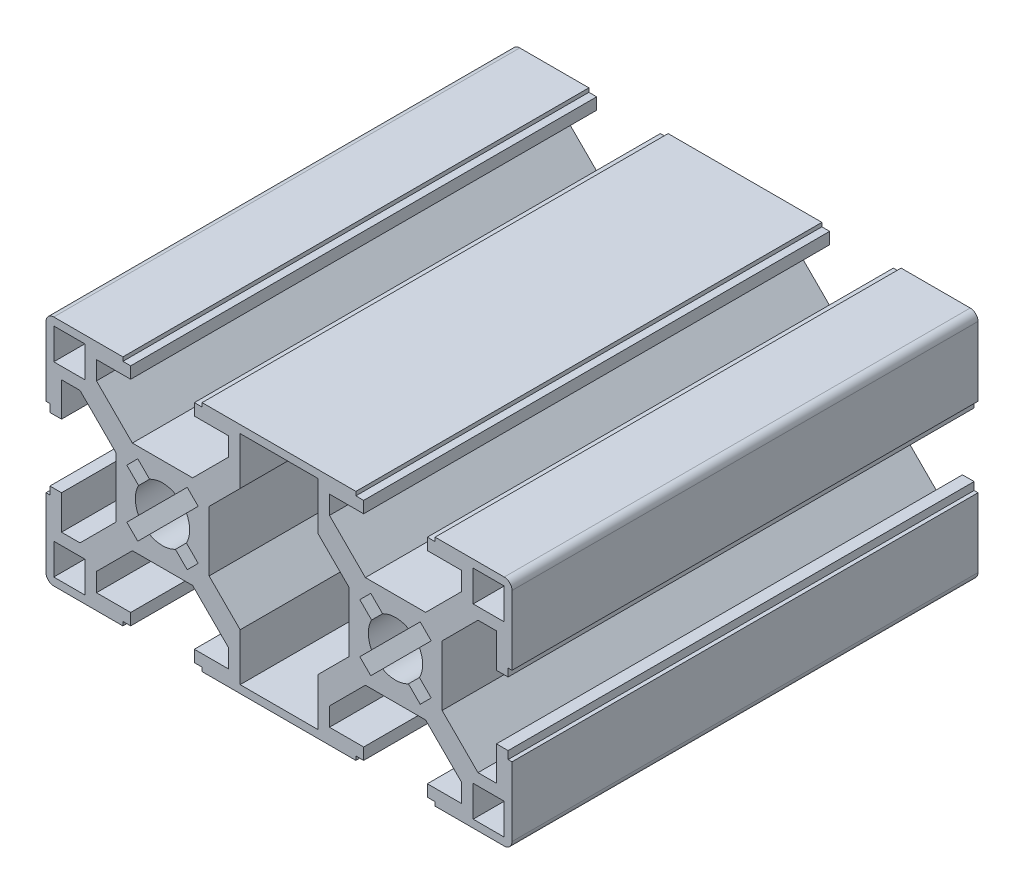
SolidWorks part; units mm, degrees
material "6063-O"
ref_plane "Plano frontal" through (0, 0, 0) normal (0, 0, 1) x (1, 0, 0)
ref_plane "Plano superior" through (0, 0, 0) normal (0, 1, 0) x (1, 0, 0)
ref_plane "Plano direito" through (0, 0, 0) normal (1, 0, 0) x (0, 0, -1)
sketch "Esboço1" plane through (0, 0, 0) normal (0, 0, 1) x (1, 0, 0)
  line L5 (0, 0) -> (-17.7944, 17.7944) construction
  line L6 (0, 3.5) -> (0, 6)
  line L8 (0, 6) -> (-3.8787, 6)
  line L9 (-3.5, 0) -> (-6, 0)
  line L48 (-6, 0) -> (-6, 3.8787)
  line L49 (-3.8787, 6) -> (-8.5, 10.6213)
  line L50 (-6, 3.8787) -> (-10.6213, 8.5)
  line L51 (0, 0) -> (-12.921, 0) construction
  line L52 (-8.5, 13) -> (-4.1, 13)
  line L53 (-4.1, 13) -> (-4.1, 14.5)
  line L54 (-4.1, 14.5) -> (-5.1, 14.5)
  line L55 (-5.1, 14.5) -> (-5.1, 15)
  line L56 (-5.1, 15) -> (-15, 15)
  line L57 (-15, 5.1) -> (-15, 15)
  line L58 (-14.5, 5.1) -> (-15, 5.1)
  line L59 (-14.5, 4.1) -> (-14.5, 5.1)
  line L60 (-13, 4.1) -> (-14.5, 4.1)
  line L61 (-13, 8.5) -> (-13, 4.1)
  line L62 (-1.6646, 3.0788) -> (-3.182, 4.5962)
  line L63 (-3.0788, 1.6646) -> (-4.5962, 3.182)
  line L64 (-4.5962, 3.182) -> (-3.182, 4.5962)
  line L65 (-8.5, 13) -> (-8.5, 10.6213)
  line L66 (-10, 14) -> (-14, 14)
  line L67 (-10, 14) -> (-10, 10)
  line L68 (-10, 10) -> (-14, 10)
  line L69 (-14, 14) -> (-14, 10)
  line L70 (-10, 14) -> (-14, 10) construction
  line L71 (-10, 10) -> (-14, 14) construction
  line L72 (-13, 8.5) -> (-10.6213, 8.5)
  circle A1 centre (0, 0) radius 3.5
  point P25 (-12, 12)
  dimension "D5" = 10.9
  dimension "D9" = 5.5
  dimension "D10" = 2
  dimension "D11" = 4
  dimension "D12" = 4
  dimension "D13" = 1
  dimension "D1" = 7
  dimension "D2" = 6
  dimension "D3" = 3
  dimension "D4" = 9.9
  dimension "D6" = 0.5
  dimension "D7" = 1.5
  dimension "D8" = 15
  dimension "D14" = 6.5
extrude "Ressalto-extrusão1" add sketch "Esboço1" along normal blind 60 contours A1 L6 L8 L49 L65 L52 L53 L54 L55 L56 L57 L58 L59 L60 L61 L72 L50 L48 L9 L63 L64 L62 L69 L66 L67 L68
sketch "Esboço3" plane through (0, 0, 0) normal (1, 0, 0) x (0, 0, -1)
  line L0 (0, 0) -> (-1000, 0) construction
  dimension "D1" = 1000
pattern_circular "PadrãoCircular1" count 4 every 90 about axis through (0, 0, 0) along (0, 0, 1) of "Ressalto-extrusão1"
pattern_linear "Padrão linear1" count 2 spacing 30 along (1, 0, 0) of "Ressalto-extrusão1", "PadrãoCircular1"
sketch "Esboço4" plane through (0, 0, 0) normal (0, 0, -1) x (-1, 0, 0)
  line L0 (-20, 14) -> (-20, -14)
  line L1 (-20, -14) -> (-10, -14)
  line L2 (-10, -14) -> (-10, 14)
  line L3 (-10, 14) -> (-20, 14)
extrude "Corte-extrusão1" cut sketch "Esboço4" against normal through all
fillet "Filete1" radius 1 4 edges at (45, -15, 30) (45, 15, 30) (-15, 15, 30) (-15, -15, 30)
